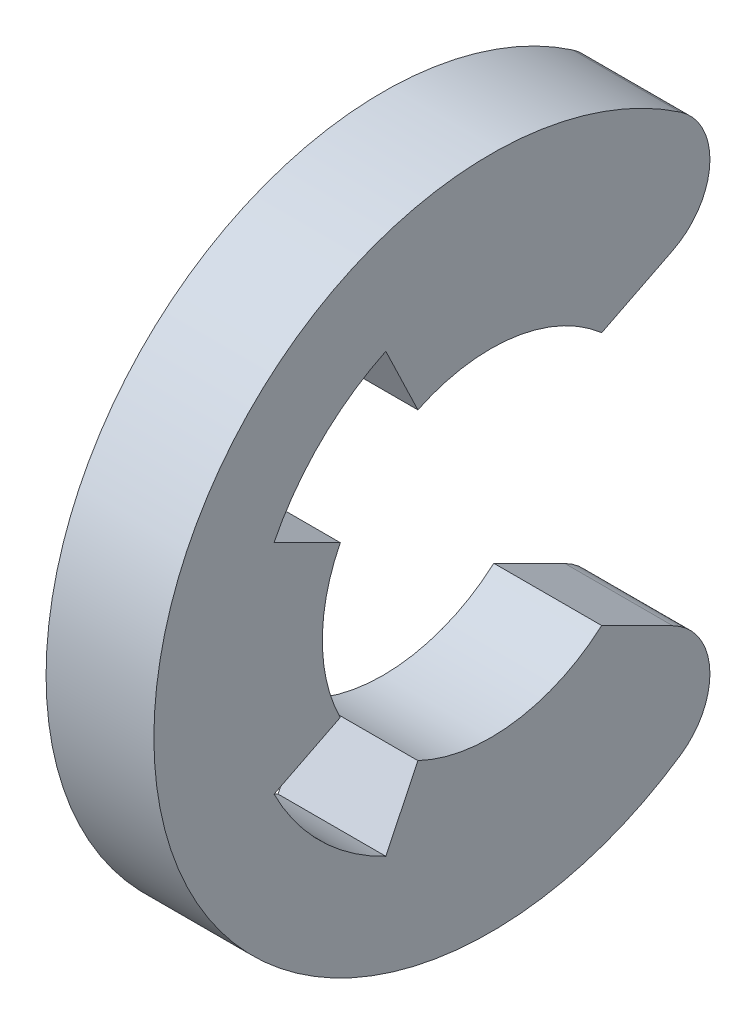
SolidWorks part; units mm, degrees
ref_plane "前视基准面" through (0, 0, 0) normal (1, 0, 0) x (0, 1, 0)
ref_plane "上视基准面" through (0, 0, 0) normal (0, 0, 1) x (0, 1, 0)
ref_plane "右视基准面" through (0, 0, 0) normal (0, 1, 0) x (-1, 0, 0)
other "Configuration Table"
sketch "草图1" plane through (0, 0, 0) normal (1, 0, 0) x (0, 1, 0)
  line L0 (0, 0) -> (-1.6228, 0.7788) construction
  line L1 (0, 0) -> (-0.8088, 1.6081) construction
  line L2 (-0.9409, -0.823) -> (-1.5233, -1.9823)
  line L3 (-1.1269, 0.5409) -> (-1.6228, 0.7788)
  line L4 (-0.5616, 1.1167) -> (-0.8088, 1.6081)
  line L5 (0, 2.5) -> (0, -2.5) construction
  line L6 (0.9409, -0.823) -> (1.5233, -1.9823)
  line L7 (0.5616, 1.1167) -> (0.8088, 1.6081)
  line L8 (1.1269, 0.5409) -> (1.6228, 0.7788)
  circle A0 centre (0, 0) radius 1.25 construction
  circle A1 centre (0, 0) radius 2.5 construction
  arc A2 (-1.1269, 0.5409) -> (-0.9409, -0.823) centre (0, 0) ccw
  arc A3 (0.5616, 1.1167) -> (-0.5616, 1.1167) centre (0, 0) ccw
  arc A4 (-1.5233, -1.9823) -> (1.5233, -1.9823) centre (0, 0) cw
  arc A5 (-1.6228, 0.7788) -> (-0.8088, 1.6081) centre (0, 0) cw
  arc A6 (1.1269, 0.5409) -> (0.9409, -0.823) centre (0, 0) cw
  arc A7 (1.6228, 0.7788) -> (0.8088, 1.6081) centre (0, 0) ccw
  dimension "D1" = 2.5
  dimension "D2" = 5
  dimension "D3" = 1.8
extrude "凸台-拉伸1" add sketch "草图1" along normal blind 0.8
fillet "圆角1" radius 0.5 2 edges at (0.4, 1.5233, -1.9823) (0.4, -1.5233, -1.9823)
